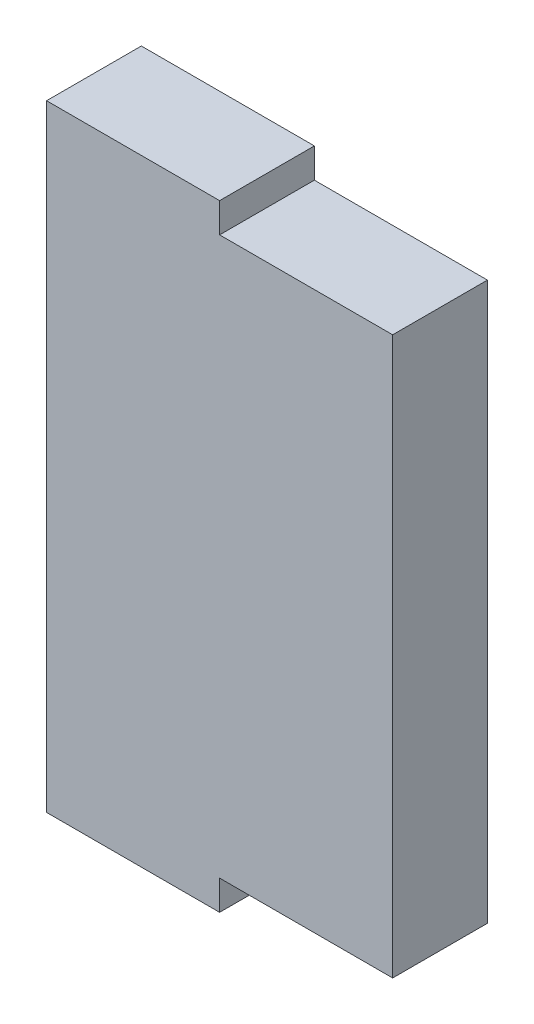
SolidWorks part; units mm, degrees
ref_plane "Front Plane" through (0, 0, 0) normal (0, 0, 1) x (1, 0, 0)
ref_plane "Top Plane" through (0, 0, 0) normal (0, 1, 0) x (1, 0, 0)
ref_plane "Right Plane" through (0, 0, 0) normal (1, 0, 0) x (0, 0, -1)
sketch "Sketch2" plane through (0, 0, 0) normal (0, 0, 1) x (1, 0, 0)
  line L0 (-105, 68) -> (-105, -306)
  line L1 (-105, -306) -> (0, -306)
  line L2 (0, -306) -> (0, -288)
  line L3 (0, -288) -> (105, -288)
  line L4 (105, -288) -> (105, 50)
  line L5 (105, 50) -> (0, 50)
  line L6 (0, 50) -> (0, 68)
  line L7 (0, 68) -> (-105, 68)
extrude "Boss-Extrude1" add sketch "Sketch2" along normal blind 57.5
